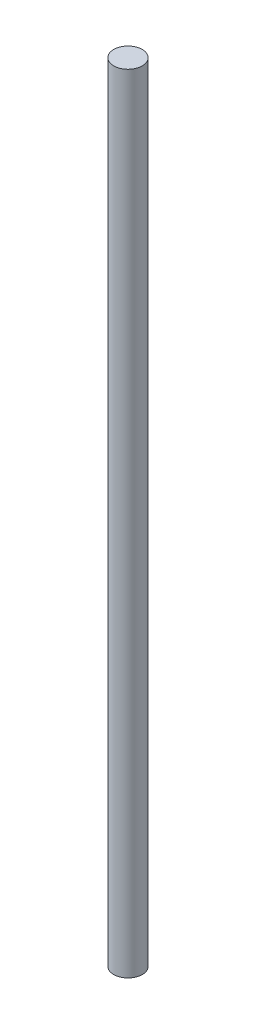
SolidWorks part; units mm, degrees
ref_plane "Front Plane" through (0, 0, 0) normal (0, 0, 1) x (1, 0, 0)
ref_plane "Top Plane" through (0, 0, 0) normal (0, 1, 0) x (1, 0, 0)
ref_plane "Right Plane" through (0, 0, 0) normal (1, 0, 0) x (0, 0, -1)
sketch "Sketch1" plane through (0, 0, 0) normal (0, 1, 0) x (1, 0, 0)
  circle A0 centre (0, 0) radius 2.5
  dimension "D1" = 5
extrude "Body" add sketch "Sketch1" along normal blind 138
